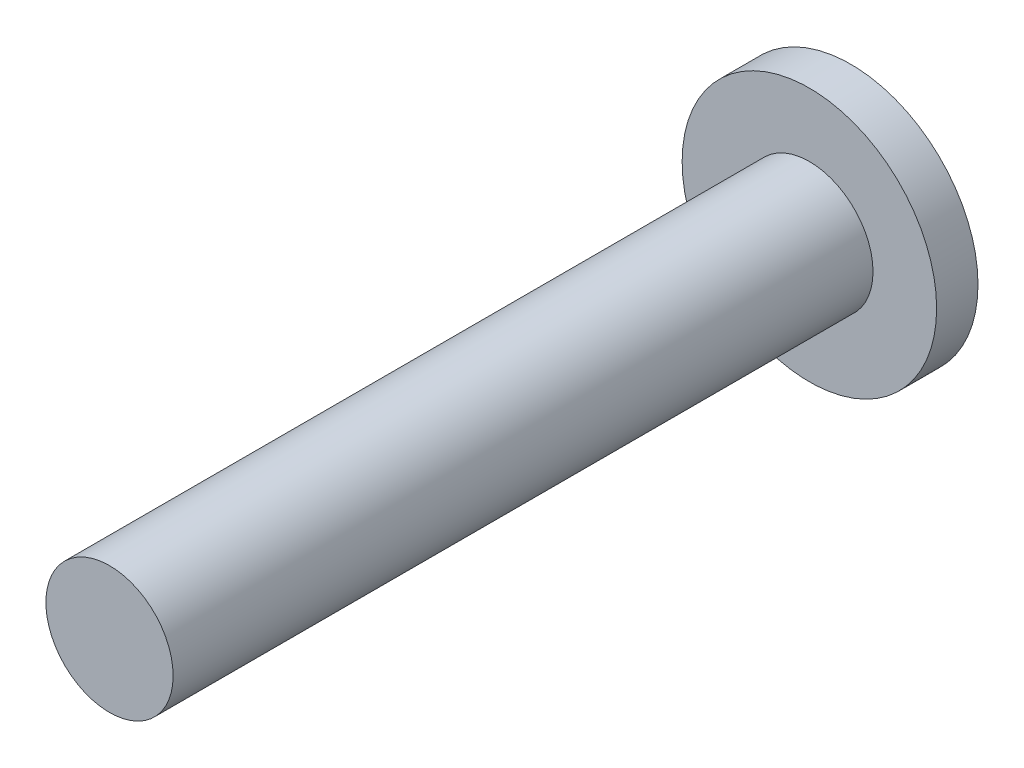
SolidWorks part; units mm, degrees
material "AISI 304"
ref_plane "前视基准面" through (0, 0, 0) normal (0, 0, 1) x (1, 0, 0)
ref_plane "上视基准面" through (0, 0, 0) normal (0, 1, 0) x (1, 0, 0)
ref_plane "右视基准面" through (0, 0, 0) normal (1, 0, 0) x (0, 0, -1)
other "Configuration Table"
sketch "草图1" plane through (0, 0, 0) normal (0, 0, 1) x (1, 0, 0)
  circle A0 centre (0, 0) radius 4
  dimension "D1" = 8
extrude "凸台-拉伸1" add sketch "草图1" along normal blind 1.3
sketch "草图2" plane through (0, 0, 1.3) normal (0, 0, 1) x (1, 0, 0)
  circle A0 centre (0, 0) radius 2
  dimension "D1" = 4
extrude "凸台-拉伸2" add sketch "草图2" along normal blind 22
sketch "草图3" plane through (0, 0, 0) normal (0, 0, -1) x (-1, 0, 0)
  line L1 (1.4434, 0) -> (0.7217, 1.25)
  line L2 (0.7217, 1.25) -> (-0.7217, 1.25)
  line L3 (-0.7217, 1.25) -> (-1.4434, 0)
  line L4 (-1.4434, 0) -> (-0.7217, -1.25)
  line L5 (-0.7217, -1.25) -> (0.7217, -1.25)
  line L6 (0.7217, -1.25) -> (1.4434, 0)
  circle A0 centre (0, 0) radius 1.25 construction
extrude "切除-拉伸1" cut sketch "草图3" against normal blind 1
